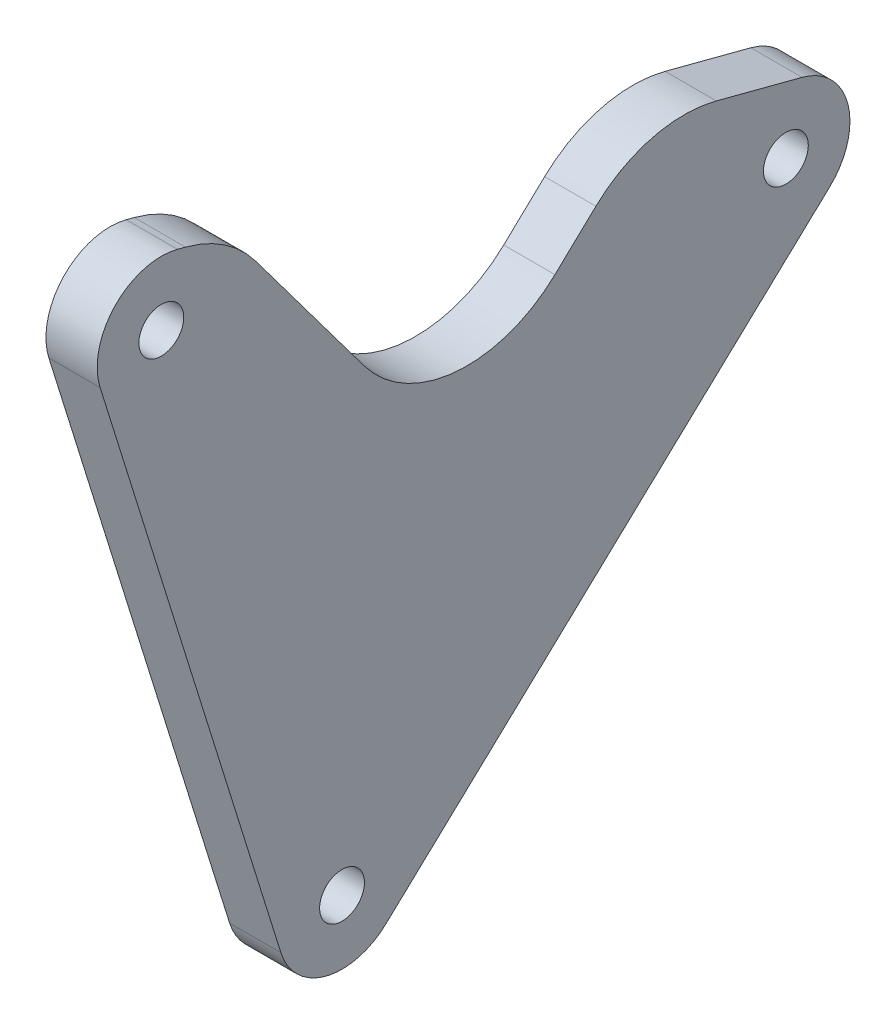
SolidWorks part; units mm, degrees
ref_plane "Piano frontale" through (0, 0, 0) normal (0, 0, 1) x (1, 0, 0)
ref_plane "Piano superiore" through (0, 0, 0) normal (0, 1, 0) x (1, 0, 0)
ref_plane "Piano destro" through (0, 0, 0) normal (1, 0, 0) x (0, 0, -1)
sketch "Schizzo2" plane through (0, 0, 0) normal (1, 0, 0) x (0, 0, -1)
  line L0 (17.4434, -4.5621) -> (18.6929, -4.8889)
  line L1 (119.255, -47.0297) -> (49.9692, -112.0297)
  line L2 (33.5805, -107.713) -> (5.3663, -17.213)
  line L3 (29.644, -12.2537) -> (46.6, -34.9078)
  line L4 (76.3654, -37.4436) -> (82.7535, -31.3928)
  line L5 (101.5677, -26.5639) -> (114.9434, -30.0621)
  arc A0 (49.9692, -112.0297) -> (33.5805, -107.713) centre (43.1273, -104.7367) cw
  arc A1 (119.255, -47.0297) -> (114.9434, -30.0621) centre (112.4131, -39.7367) ccw
  arc A2 (5.3663, -17.213) -> (17.4434, -4.5621) centre (14.9131, -14.2367) cw
  circle A3 centre (14.9131, -14.2367) radius 3.5
  circle A4 centre (112.4131, -39.7367) radius 3.5
  circle A5 centre (43.1273, -104.7367) radius 3.5
  arc A6 (18.6929, -4.8889) -> (29.644, -12.2537) centre (13.6323, -24.2381) cw
  arc A7 (82.7535, -31.3928) -> (101.5677, -26.5639) centre (96.5071, -45.913) cw
  arc A8 (76.3654, -37.4436) -> (46.6, -34.9078) centre (62.6117, -22.9234) cw
  point P10 (0, 0)
  point P21 (90.8194, -23.7528)
  dimension "D1" = 10
  dimension "D5" = 7
  dimension "D6" = 7
  dimension "D7" = 7
  dimension "D8" = 20
  dimension "D9" = 20
  dimension "D10" = 20
  dimension "D2" = 97.5
  dimension "D3" = 25.5
  dimension "D4" = 65
extrude "Estrusione-Estrusione1" add sketch "Schizzo2" along normal blind 8
